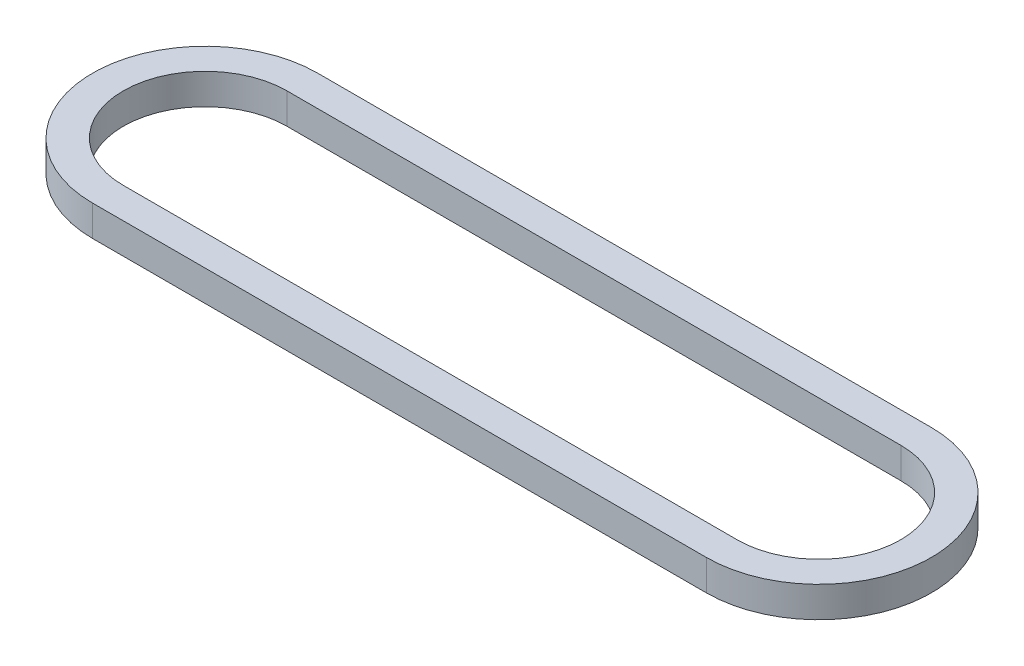
SolidWorks part; units mm, degrees
ref_plane "Front Plane" through (0, 0, 0) normal (0, 0, 1) x (1, 0, 0)
ref_plane "Top Plane" through (0, 0, 0) normal (0, 1, 0) x (1, 0, 0)
ref_plane "Right Plane" through (0, 0, 0) normal (1, 0, 0) x (0, 0, -1)
sketch "Sketch1" plane through (0, 0, 0) normal (0, 1, 0) x (1, 0, 0)
  line L0 (-76.2, 0) -> (76.2, 0) construction
  line L1 (-76.2, 20.32) -> (76.2, 20.32)
  line L2 (-76.2, -20.32) -> (76.2, -20.32)
  line L3 (-76.2, 27.94) -> (76.2, 27.94)
  line L4 (-76.2, -27.94) -> (76.2, -27.94)
  arc A0 (-76.2, 20.32) -> (-76.2, -20.32) centre (-76.2, 0) ccw
  arc A1 (76.2, -20.32) -> (76.2, 20.32) centre (76.2, 0) ccw
  arc A2 (76.2, -27.94) -> (76.2, 27.94) centre (76.2, 0) ccw
  arc A3 (-76.2, 27.94) -> (-76.2, -27.94) centre (-76.2, 0) ccw
  point P2 (0, 0)
  dimension "D1" = 20.32
  dimension "D2" = 152.4
  dimension "D3" = 7.62
extrude "Boss-Extrude1" add sketch "Sketch1" along normal blind 7.62
